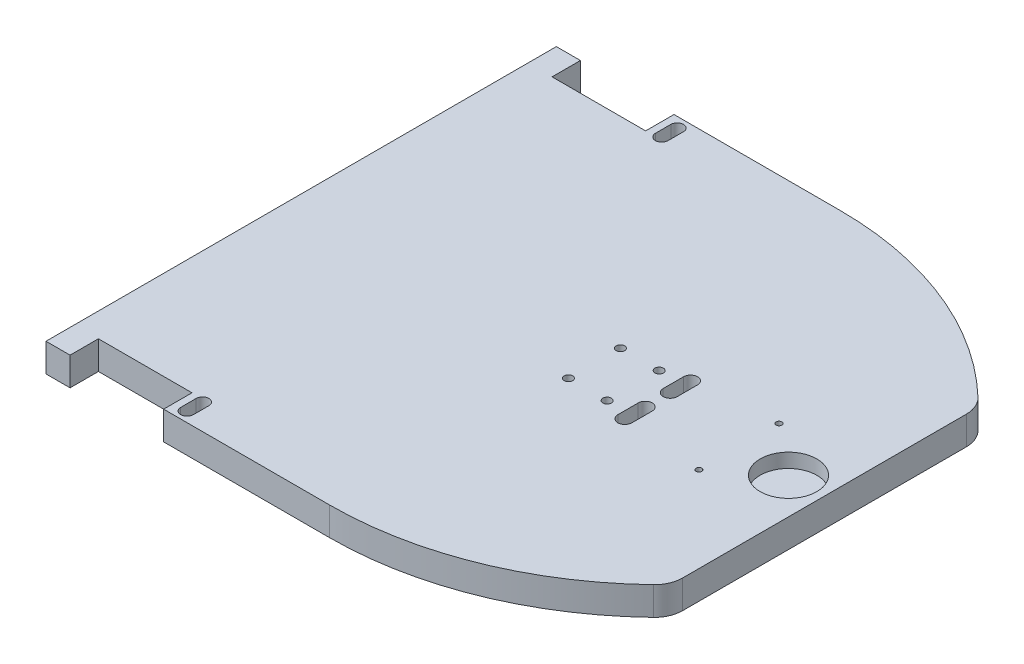
SolidWorks part; units mm, degrees
ref_plane "Front Plane" through (0, 0, 0) normal (0, 0, 1) x (1, 0, 0)
ref_plane "Top Plane" through (0, 0, 0) normal (0, 1, 0) x (1, 0, 0)
ref_plane "Right Plane" through (0, 0, 0) normal (1, 0, 0) x (0, 0, -1)
sketch "Sketch1" plane through (0, 0, 0) normal (0, 1, 0) x (1, 0, 0)
  line L0 (-89.3891, 0) -> (95.1826, 0) construction
  line L1 (-89.3891, -90) -> (-89.3891, 90)
  line L2 (-89.3891, 90) -> (10.6109, 90)
  line L3 (95.1826, 50) -> (95.1826, -50)
  line L4 (-89.3891, -90) -> (10.6109, -90)
  arc A0 (10.6109, 90) -> (92.1078, 57.214) centre (10.6109, -27.6825) cw
  arc A1 (92.1078, 57.214) -> (95.1826, 50) centre (85.1826, 50) cw
  arc A2 (92.1078, -57.214) -> (95.1826, -50) centre (85.1826, -50) ccw
  arc A3 (10.6109, -90) -> (92.1078, -57.214) centre (10.6109, 27.6825) ccw
  dimension "D1" = 10
  dimension "D2" = 180
  dimension "D3" = 100
  dimension "D4" = 100
extrude "Boss-Extrude1" add sketch "Sketch1" along normal blind 10
sketch "Sketch2" plane through (0, 10, 0) normal (0, 1, 0) x (1, 0, 0)
  line L0 (-89.3891, 0) -> (95.1826, 0) construction
  line L1 (-89.3891, 90) -> (-89.3891, -90) construction
  line L2 (95.1826, -50) -> (95.1826, 50) construction
  line L4 (36.3663, -11.5949) -> (36.3663, -4.4051) construction
  line L7 (-43.2044, 86.4271) -> (-43.2044, 80.9729) construction
  line L8 (-40.9689, 86.4271) -> (-40.9689, 80.9729)
  line L9 (-45.4398, 86.4271) -> (-45.4398, 80.9729)
  line L10 (36.3663, 11.5949) -> (36.3663, 4.4051) construction
  line L11 (38.8455, 11.5949) -> (38.8455, 4.4051)
  line L12 (33.887, 11.5949) -> (33.887, 4.4051)
  line L14 (10.6109, 90) -> (-89.3891, 90) construction
  line L15 (-80.901, 90) -> (-47.901, 90)
  line L16 (-80.901, 90) -> (-80.901, 80)
  line L17 (-80.901, 80) -> (-47.901, 80)
  line L18 (-47.901, 90) -> (-47.901, 80)
  line L19 (38.8455, -11.5949) -> (38.8455, -4.4051)
  line L20 (33.887, -11.5949) -> (33.887, -4.4051)
  line L21 (-43.2044, -86.4271) -> (-43.2044, -80.9729) construction
  line L22 (-40.9689, -86.4271) -> (-40.9689, -80.9729)
  line L23 (-45.4398, -86.4271) -> (-45.4398, -80.9729)
  line L24 (-80.901, -80) -> (-47.901, -80)
  line L25 (-47.901, -90) -> (-47.901, -80)
  line L26 (-80.901, -90) -> (-47.901, -90)
  line L27 (-80.901, -90) -> (-80.901, -80)
  circle A0 centre (65, 14.1316) radius 1
  circle A1 centre (27.689, 9.1731) radius 1.5
  circle A2 centre (14.0532, 9.1731) radius 1.5
  arc A3 (-40.9689, 86.4271) -> (-45.4398, 86.4271) centre (-43.2044, 86.4271) ccw
  arc A4 (-45.4398, 80.9729) -> (-40.9689, 80.9729) centre (-43.2044, 80.9729) ccw
  arc A5 (38.8455, 11.5949) -> (33.887, 11.5949) centre (36.3663, 11.5949) ccw
  arc A6 (33.887, 4.4051) -> (38.8455, 4.4051) centre (36.3663, 4.4051) ccw
  circle A7 centre (14.0532, -9.1731) radius 1.5
  circle A8 centre (27.689, -9.1731) radius 1.5
  circle A9 centre (65, -14.1316) radius 1
  arc A10 (38.8455, -11.5949) -> (33.887, -11.5949) centre (36.3663, -11.5949) cw
  arc A11 (33.887, -4.4051) -> (38.8455, -4.4051) centre (36.3663, -4.4051) cw
  arc A12 (-40.9689, -86.4271) -> (-45.4398, -86.4271) centre (-43.2044, -86.4271) cw
  arc A13 (-45.4398, -80.9729) -> (-40.9689, -80.9729) centre (-43.2044, -80.9729) cw
  point P20 (-43.2044, 83.7)
  point P25 (36.3663, 8)
  point P32 (0, 0)
  point P41 (36.3663, -8)
  point P48 (-43.2044, -83.7)
  dimension "D1" = 10
  dimension "D2" = 33
extrude "Cut-Extrude2" cut sketch "Sketch2" against normal mid plane 30 contours L17 L18 L15 L16 | L24 L25 L26 L27 | L19 A11 L20 A10 | L11 A6 L12 A5 | A1 | A2 | A7 | A8 | A9 | A0 | L8 A4 L9 A3 | L22 A13 L23 A12
sketch "Sketch3" plane through (0, 10, 0) normal (0, 1, 0) x (1, 0, 0)
  line L0 (12.3178, 0) -> (112.2305, 0) construction
  circle A0 centre (82.4798, 0) radius 10
extrude "Cut-Extrude3" cut sketch "Sketch3" against normal mid plane 10
